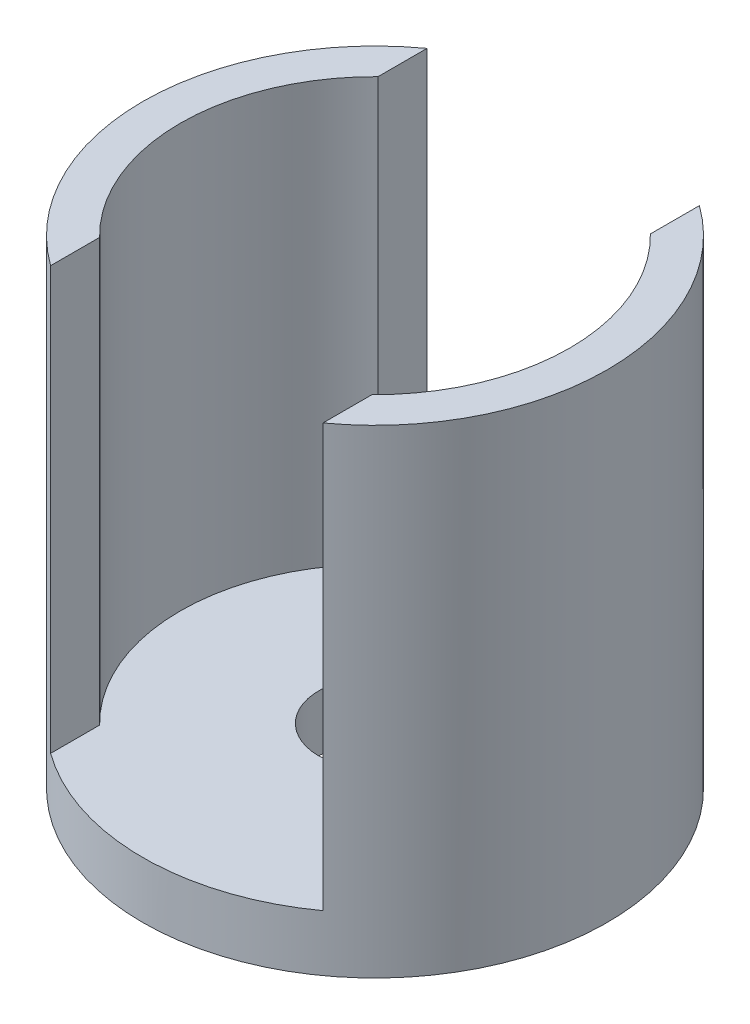
SolidWorks part; units mm, degrees
ref_plane "Front Plane" through (0, 0, 0) normal (0, 0, 1) x (1, 0, 0)
ref_plane "Top Plane" through (0, 0, 0) normal (0, 1, 0) x (1, 0, 0)
ref_plane "Right Plane" through (0, 0, 0) normal (1, 0, 0) x (0, 0, -1)
sketch "Sketch2" plane through (0, 0, 0) normal (0, 1, 0) x (1, 0, 0)
  circle A0 centre (0, 0) radius 2
  circle A1 centre (0, 0) radius 8.25
  dimension "D1" = 4
  dimension "D2" = 16.5
extrude "Boss-Extrude1" add sketch "Sketch2" along normal blind 2
sketch "Sketch3" plane through (0, 2, 0) normal (0, 1, 0) x (1, 0, 0)
  line L1 (-4.8368, -8.1055) -> (4.8368, -8.1055)
  line L2 (-4.8368, -8.1055) -> (-4.8368, 8.1055)
  line L3 (-4.8368, 8.1055) -> (4.8368, 8.1055)
  line L4 (4.8368, -8.1055) -> (4.8368, 8.1055)
  line L5 (-4.8368, -8.1055) -> (4.8368, 8.1055) construction
  line L6 (-4.8368, 8.1055) -> (4.8368, -8.1055) construction
  circle A0 centre (0, 0) radius 8.25
  circle A1 centre (0, 0) radius 6.9158
  circle M5 centre (0, 0) radius 8.25
extrude "Boss-Extrude2" add sketch "Sketch3" along normal blind 15 contours A1 L2 M5 | A1 L4 M5
